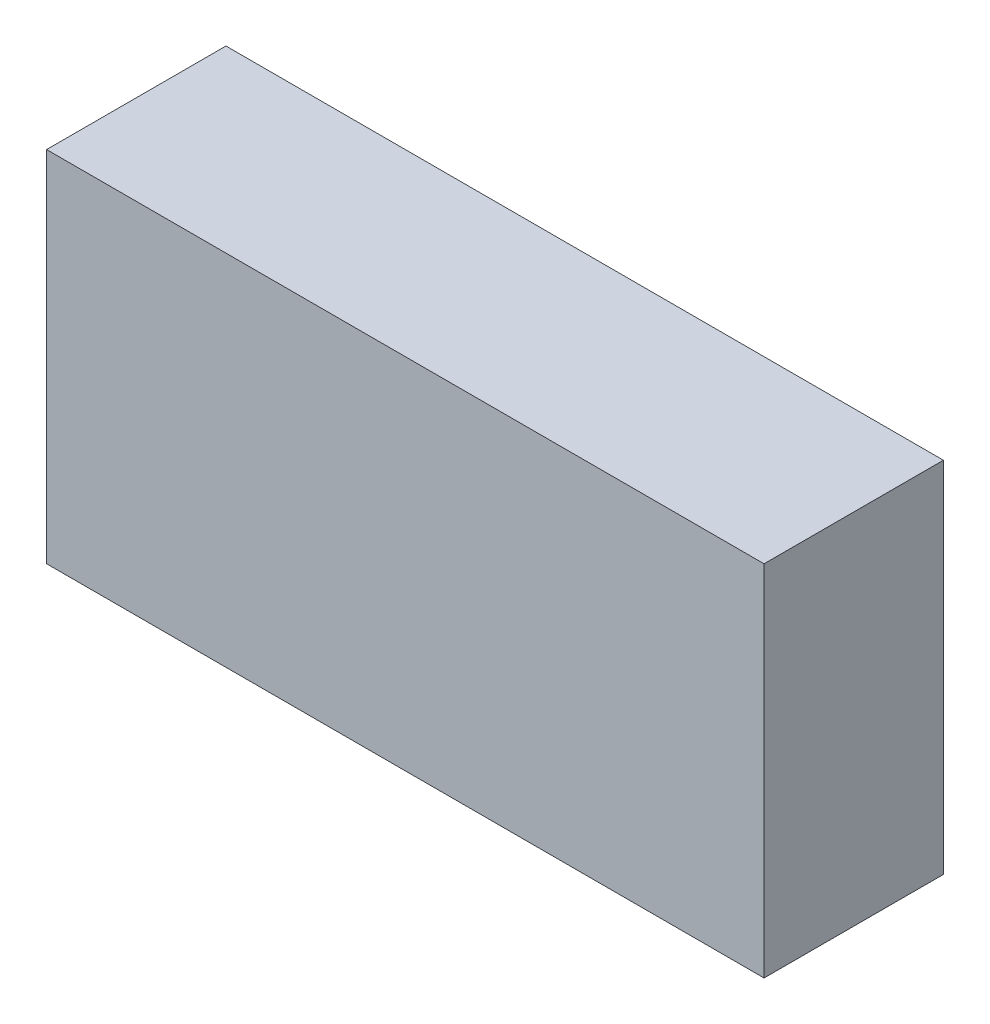
SolidWorks part; units mm, degrees
ref_plane "Front Plane" through (0, 0, 0) normal (0, 0, 1) x (1, 0, 0)
ref_plane "Top Plane" through (0, 0, 0) normal (0, 1, 0) x (1, 0, 0)
ref_plane "Right Plane" through (0, 0, 0) normal (1, 0, 0) x (0, 0, -1)
sketch "Sketch1" plane through (0, 0, 0) normal (0, 0, 1) x (1, 0, 0)
  line L0 (-0.775, 0.425) -> (0.825, 0.425)
  line L1 (0.825, 0.425) -> (0.825, -0.375)
  line L2 (0.825, -0.375) -> (-0.775, -0.375)
  line L3 (-0.775, -0.375) -> (-0.775, 0.425)
extrude "Component_Outline" add sketch "Sketch1" along normal blind 0.4 separate body
sketch3d "3DSketch1"
  line L0 (0, 0, 0) -> (1, 0, 0)
  line L1 (0, 0, 0) -> (0, 1, 0)
  line L2 (0, 0, 0) -> (0, 0, 1)
  point P0 (0, 0, 0)
